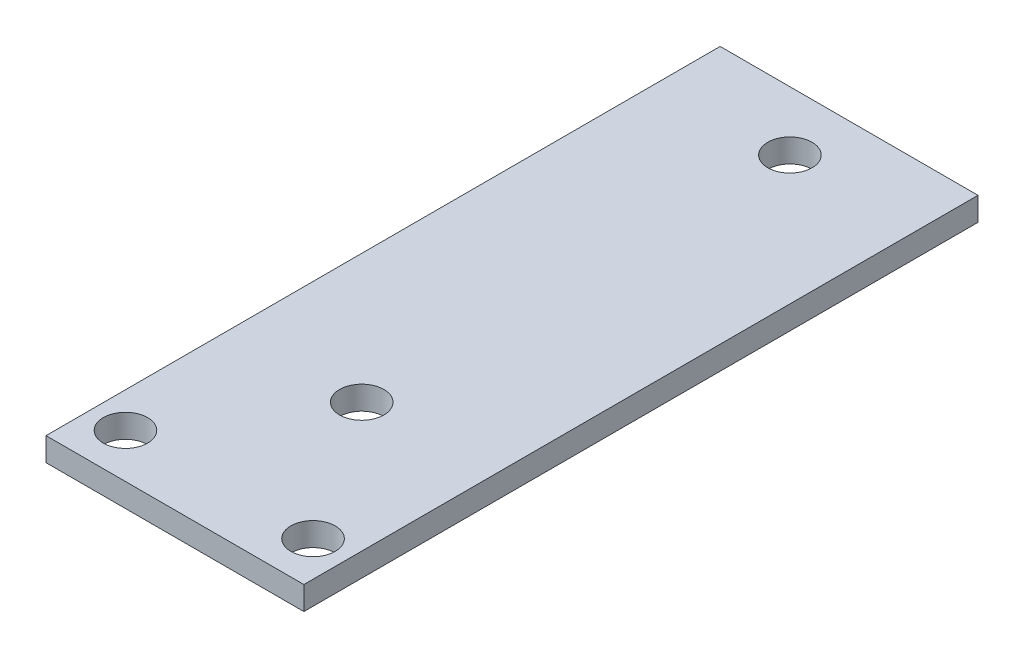
SolidWorks part; units mm, degrees
material "1060 Alloy"
ref_plane "Front Plane" through (0, 0, 0) normal (0, 0, 1) x (1, 0, 0)
ref_plane "Top Plane" through (0, 0, 0) normal (0, 1, 0) x (1, 0, 0)
ref_plane "Right Plane" through (0, 0, 0) normal (1, 0, 0) x (0, 0, -1)
ref_plane "Plane1" through (0, -34.925, 0) normal (0, -1, 0) x (1, 0, 0)
sketch "Sketch1" plane through (0, -34.925, 0) normal (0, -1, 0) x (1, 0, 0)
  line L0 (-3.175, -115) -> (34.925, -115)
  line L1 (34.925, -115) -> (34.925, 5)
  line L2 (34.925, 5) -> (-3.175, 5)
  line L3 (-3.175, 5) -> (-3.175, -115)
extrude "Boss-Extrude1" add sketch "Sketch1" against normal blind 38.1
sketch "Sketch2" plane through (0, 0, -115) normal (0, 0, -1) x (-1, 0, 0)
  line L0 (-34.925, -34.925) -> (0, -34.925)
  line L1 (0, -34.925) -> (0, 0)
  line L2 (0, 0) -> (-34.925, 0)
  line L3 (-34.925, 0) -> (-34.925, -34.925)
extrude "Cut-Extrude1" cut sketch "Sketch2" against normal through all
sketch "Sketch18" plane through (0, 0, 5) normal (0, 0, 1) x (1, 0, 0)
  line L1 (-3.175, 3.175) -> (0, 3.175)
  line L2 (-3.175, 3.175) -> (-3.175, 0)
  line L3 (-3.175, 0) -> (0, 0)
  line L4 (0, 3.175) -> (0, 0)
extrude "Cut-Extrude3" cut sketch "Sketch18" against normal through all
sketch "Sketch19" plane through (0, 0, 0) normal (0, -1, 0) x (1, 0, 0)
  line L0 (17.4625, 5) -> (17.4625, -115) construction
  line L1 (0, 5) -> (34.925, 5) construction
  line L2 (0, -115) -> (34.925, -115) construction
  line L3 (17.4625, -6) -> (0, -6) construction
  line L4 (0, 5) -> (0, -115) construction
  line L5 (17.4625, -6) -> (34.925, -6) construction
  line L6 (34.925, 5) -> (34.925, -115) construction
  circle A0 centre (17.4625, -93.8) radius 3
  circle A1 centre (17.4625, -33.8) radius 3
  circle A3 centre (4.7625, -6) radius 3
  circle A4 centre (30.1625, -6) radius 3
  circle A5 centre (17.4625, -83.29) radius 3
  circle A6 centre (17.4625, -25.3) radius 3
  dimension "D1" = 6
  dimension "D2" = 6
  dimension "D3" = 12.7
  dimension "D4" = 21.2
  dimension "D6" = 12.7
  dimension "D5" = 81.2
  dimension "D7" = 6
  dimension "D8" = 6
  dimension "D9" = 109
  dimension "D12" = 6
  dimension "D13" = 6
  dimension "D10" = 31.71
  dimension "D11" = 89.7
extrude "Cut-Extrude4" cut sketch "Sketch19" against normal through all contours A4 | A3 | A6 | A5
sketch "Sketch20" plane through (0, 0, 0) normal (0, -1, 0) x (1, 0, 0)
  line L2 (0, 0) -> (34.925, 0)
  line L3 (0, 0) -> (34.925, 0)
  line L4 (0, 5) -> (34.925, 5)
  line L5 (0, 5) -> (0, 0)
  line L6 (0, 0) -> (34.925, 0)
  line L7 (34.925, 5) -> (34.925, 0)
  line M7 (34.925, -115) -> (34.925, 5)
  line M8 (34.925, 5) -> (0, 5)
  line M9 (0, 5) -> (0, -115)
  dimension "D1" = 5
extrude "Cut-Extrude5" cut sketch "Sketch20" against normal through all contours L3 M9 M7 M8
sketch "Sketch21" plane through (0, 0, 0) normal (0, -1, 0) x (1, 0, 0)
  line L0 (0, -115) -> (34.925, -115) construction
  line L1 (0, -115) -> (34.925, -115)
  line L2 (0, -91.3) -> (34.925, -91.3)
  line L4 (0, -91.3) -> (34.925, -91.3)
  line L5 (0, -91.3) -> (0, -115)
  line L6 (0, -115) -> (34.925, -115)
  line L7 (34.925, -91.3) -> (34.925, -115)
  line M7 (0, 0) -> (0, -115)
  line M8 (0, -115) -> (34.925, -115)
  line M9 (34.925, -115) -> (34.925, 0)
  dimension "D1" = 23.7
extrude "Cut-Extrude6" cut sketch "Sketch21" against normal through all contours L2 M7 M8 M9
